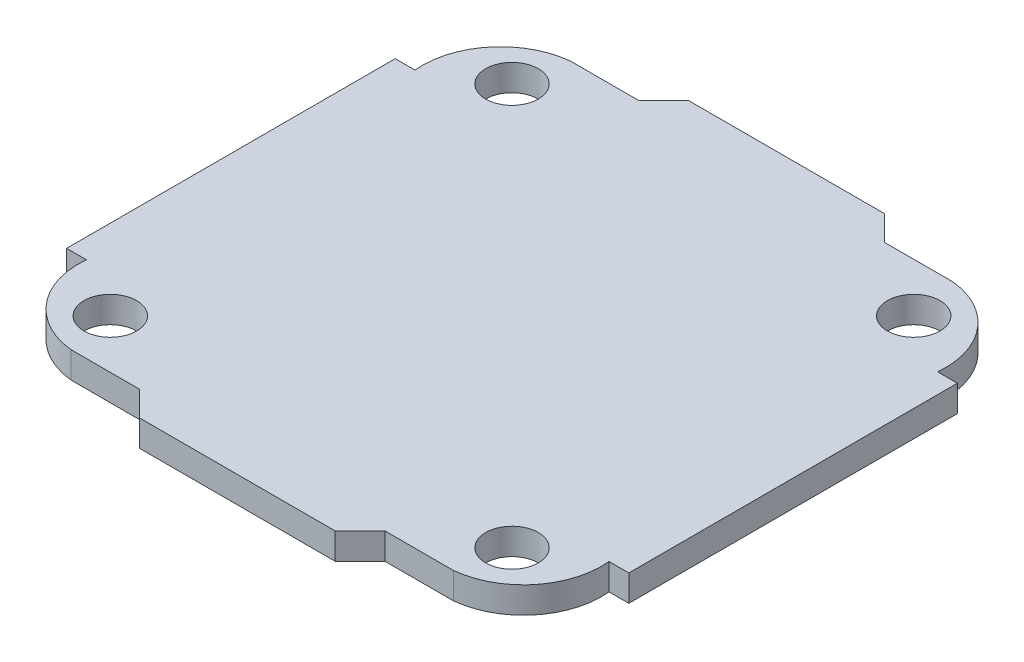
SolidWorks part; units mm, degrees
ref_plane "前视基准面" through (0, 0, 0) normal (0, 0, 1) x (1, 0, 0)
ref_plane "上视基准面" through (0, 0, 0) normal (0, 1, 0) x (1, 0, 0)
ref_plane "右视基准面" through (0, 0, 0) normal (1, 0, 0) x (0, 0, -1)
other "Configuration Table"
sketch "草图1" plane through (0, 0, 0) normal (0, 1, 0) x (1, 0, 0)
  line L0 (-19.8873, -20.8574) -> (19.8873, -20.8574)
  line L1 (19.8873, -20.8574) -> (21.3424, -19.4022)
  line L2 (21.3424, -19.4022) -> (21.3424, 19.4022)
  line L3 (21.3424, 19.4022) -> (19.8873, 20.8574)
  line L4 (19.8873, 20.8574) -> (-19.8873, 20.8574)
  line L5 (-19.8873, 20.8574) -> (-21.3424, 19.4022)
  line L6 (-21.3424, 19.4022) -> (-21.3424, -19.4022)
  line L7 (-21.3424, -19.4022) -> (-19.8873, -20.8574)
  line L8 (0, 0) -> (30.3044, 0) construction
  line L9 (0, 0) -> (0, -9.0996) construction
  circle A0 centre (15.25, 15.25) radius 2
  circle A1 centre (-15.25, 15.25) radius 2
  circle A2 centre (15.25, -15.25) radius 2
  circle A3 centre (-15.25, -15.25) radius 2
  dimension "D3" = 4
  dimension "D1" = 15.25
  dimension "D2" = 15.25
extrude "凸台-拉伸1" add sketch "草图1" along normal blind 2
sketch "草图2" plane through (0, 2, 0) normal (0, 1, 0) x (1, 0, 0)
  line L0 (0, 0) -> (39.2549, 0) construction
  line L1 (0, 0) -> (0, 29.7109) construction
  line L2 (-21.3424, 0) -> (-21.3424, 27.7318) construction
  line L4 (21.3424, 0) -> (21.3424, 27.7318) construction
  line L5 (-19.8428, 12.4739) -> (-21.3424, 12.4739)
  line L6 (-14.5123, 18.9682) -> (-9.3131, 18.9682)
  line L7 (-9.3131, 18.9682) -> (-7.4239, 20.8574)
  line L8 (19.8873, 20.8574) -> (-19.8873, 20.8574) construction
  line L9 (-7.4239, 20.8574) -> (-21.3424, 20.8574)
  line L10 (-21.3424, 20.8574) -> (-21.3424, 12.4739)
  line L11 (7.4239, 20.8574) -> (21.3424, 20.8574)
  line L12 (9.3131, 18.9682) -> (7.4239, 20.8574)
  line L13 (14.5123, 18.9682) -> (9.3131, 18.9682)
  line L14 (19.8428, 12.4739) -> (21.3424, 12.4739)
  line L15 (21.3424, 20.8574) -> (21.3424, 12.4739)
  line L16 (9.3131, -18.9682) -> (7.4239, -20.8574)
  line L17 (14.5123, -18.9682) -> (9.3131, -18.9682)
  line L18 (19.8428, -12.4739) -> (21.3424, -12.4739)
  line L19 (21.3424, -20.8574) -> (21.3424, -12.4739)
  line L20 (7.4239, -20.8574) -> (21.3424, -20.8574)
  line L21 (-7.4239, -20.8574) -> (-21.3424, -20.8574)
  line L22 (-9.3131, -18.9682) -> (-7.4239, -20.8574)
  line L23 (-14.5123, -18.9682) -> (-9.3131, -18.9682)
  line L24 (-19.8428, -12.4739) -> (-21.3424, -12.4739)
  line L25 (-21.3424, -20.8574) -> (-21.3424, -12.4739)
  arc A0 (-19.8428, 12.4739) -> (-14.5123, 18.9682) centre (-13.9304, 13.0558) cw
  arc A1 (19.8428, 12.4739) -> (14.5123, 18.9682) centre (13.9304, 13.0558) ccw
  arc A2 (19.8428, -12.4739) -> (14.5123, -18.9682) centre (13.9304, -13.0558) cw
  arc A3 (-19.8428, -12.4739) -> (-14.5123, -18.9682) centre (-13.9304, -13.0558) ccw
  dimension "D1" = 21.3424
extrude "切除-拉伸1" cut sketch "草图2" against normal through all
